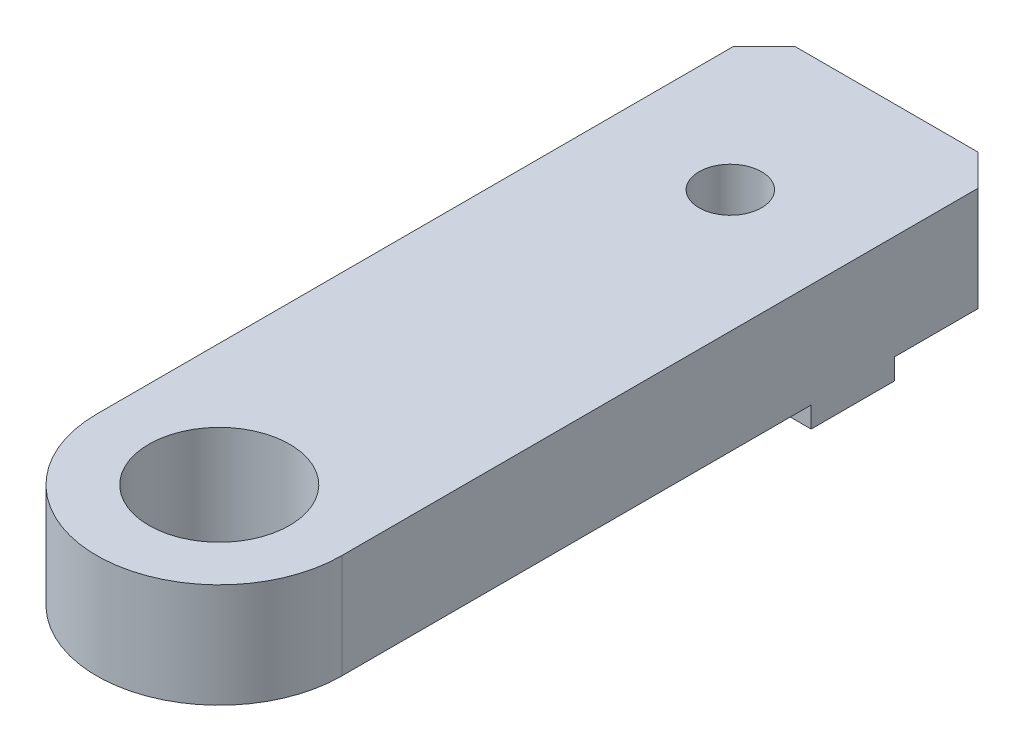
SolidWorks part; units mm, degrees
ref_plane "Front Plane" through (0, 0, 0) normal (0, 0, 1) x (1, 0, 0)
ref_plane "Top Plane" through (0, 0, 0) normal (0, 1, 0) x (1, 0, 0)
ref_plane "Right Plane" through (0, 0, 0) normal (1, 0, 0) x (0, 0, -1)
sketch "Sketch1" plane through (0, 0, 0) normal (0, 1, 0) x (1, 0, 0)
  line L0 (-11.75, 0) -> (-11.75, 64)
  line L1 (-11.75, 64) -> (11.75, 64)
  line L2 (11.75, 64) -> (11.75, 0)
  line L3 (0, 64) -> (0, 49) construction
  circle A0 centre (0, 0) radius 6.75
  circle A1 centre (0, 0) radius 11.75
  circle A2 centre (0, 49) radius 3
  dimension "D1" = 13.5
  dimension "D4" = 6
  dimension "D3" = 64
  dimension "D5" = 15
  dimension "D2" = 5
extrude "Boss-Extrude1" add sketch "Sketch1" along normal blind 10
sketch "Sketch2" plane through (0, 0, 0) normal (0, -1, 0) x (1, 0, 0)
  line L0 (11.75, -64) -> (11.75, 0) construction
  line L1 (-11.75, -53) -> (11.75, -53)
  line L2 (-11.75, -53) -> (-11.75, -45)
  line L3 (-11.75, -45) -> (11.75, -45)
  line L4 (11.75, -53) -> (11.75, -45)
  line L5 (-11.75, -53) -> (11.75, -45) construction
  line L6 (-11.75, -45) -> (11.75, -53) construction
  circle A0 centre (0, -49) radius 3 construction
  circle A1 centre (0, -49) radius 3
  point P0 (0, -49)
  dimension "D1" = 8
extrude "Boss-Extrude2" add sketch "Sketch2" along normal blind 2
chamfer "Chamfer1" distance 3 angle 45 2 edges at (11.75, 5, -64) (-11.75, 5, -64)
sketch "Sketch3" plane through (0, -2, 0) normal (0, -1, 0) x (1, 0, 0)
  circle A0 centre (0, -49) radius 6
  dimension "D1" = 12
extrude "Cut-Extrude1" cut sketch "Sketch3" against normal up to surface (2 mm away) up to face at (0, 0, 6.75)
fillet "Fillet1" radius 1 4 edges at (4.4721, -1, -53) (-4.4721, -1, -53) (4.4721, -1, -45) (-4.4721, -1, -45)
